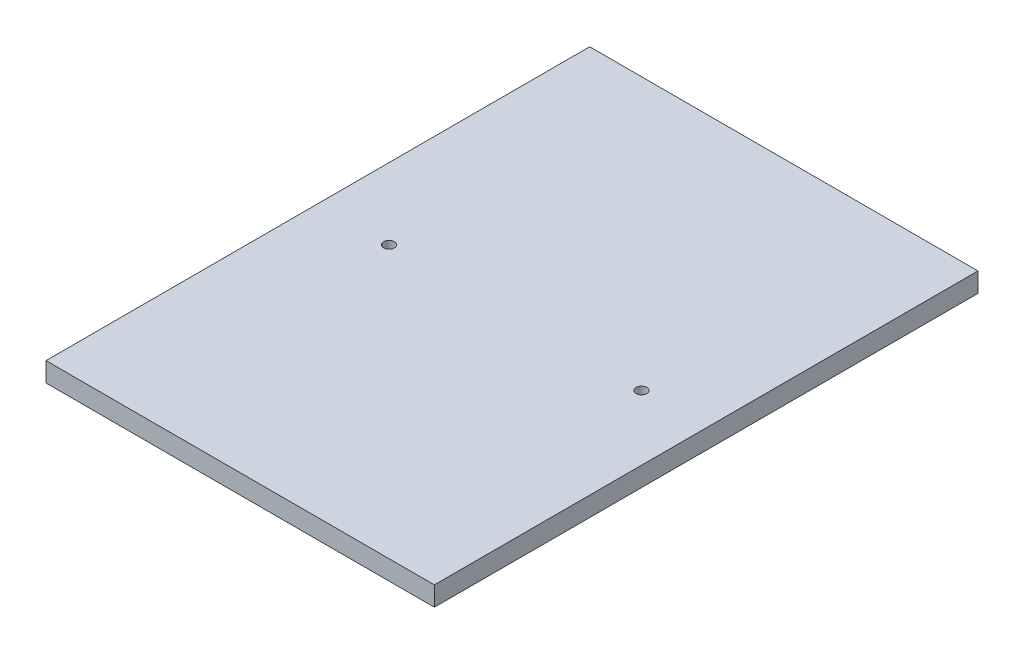
SolidWorks part; units mm, degrees
material "Poplar plywood painted"
ref_plane "Front Plane" through (0, 0, 0) normal (0, 0, 1) x (1, 0, 0)
ref_plane "Top Plane" through (0, 0, 0) normal (0, 1, 0) x (1, 0, 0)
ref_plane "Right Plane" through (0, 0, 0) normal (1, 0, 0) x (0, 0, -1)
sketch "Sketch1" plane through (0, 0, 0) normal (0, 1, 0) x (1, 0, 0)
  line L0 (-90, 126) -> (90, -126) construction
  line L1 (-90, 126) -> (90, 126)
  line L2 (-90, 126) -> (-90, -126)
  line L3 (-90, -126) -> (90, -126)
  line L4 (90, 126) -> (90, -126)
  dimension "D1" = 180
  dimension "D2" = 252
extrude "Boss-Extrude1" add sketch "Sketch1" along normal mid plane 9
sketch "Sketch2" plane through (0, 4.5, 0) normal (0, 1, 0) x (1, 0, 0)
  line L0 (60, 0) -> (-57, 0) construction
  line L2 (60, 0) -> (90, 0) construction
  line L3 (90, -126) -> (90, 126) construction
  circle A0 centre (60, 0) radius 2.5
  circle A1 centre (-57, 0) radius 2.5
  dimension "D1" = 117
  dimension "D2" = 5
  dimension "D3" = 30
extrude "Cut-Extrude1" cut sketch "Sketch2" against normal through all
